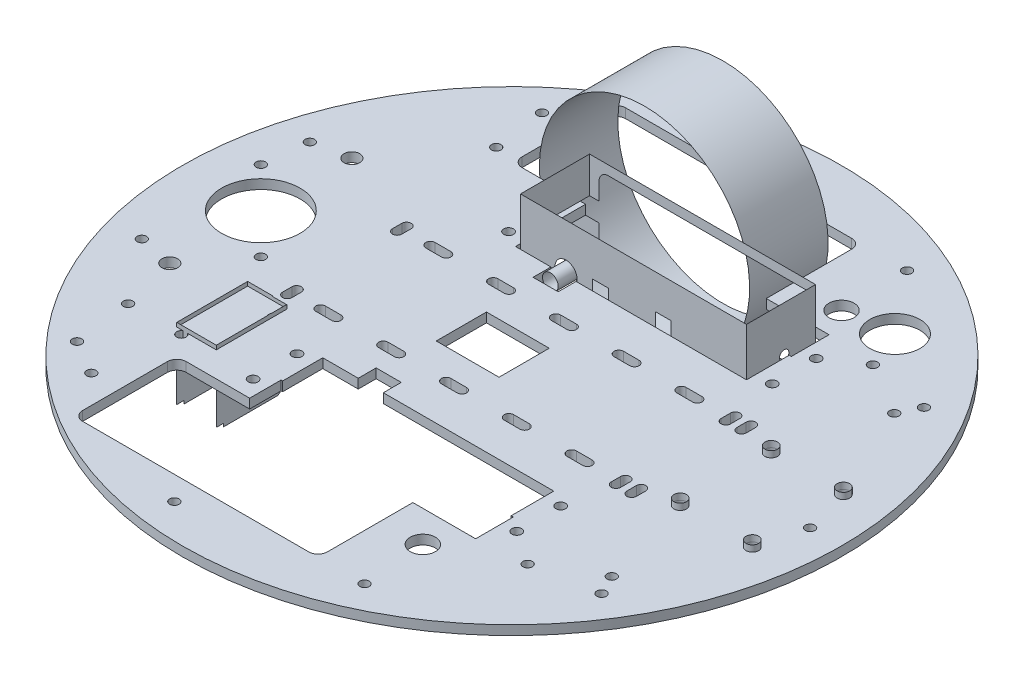
SolidWorks part; units mm, degrees
ref_plane "前基準面" through (0, 0, 0) normal (0, 0, 1) x (1, 0, 0)
ref_plane "上基準面" through (0, 0, 0) normal (0, 1, 0) x (1, 0, 0)
ref_plane "右基準面" through (0, 0, 0) normal (1, 0, 0) x (0, 0, -1)
sketch "草圖2" plane through (0, 0, 0) normal (0, 1, 0) x (1, 0, 0)
  line L1 (-60, 60) -> (60, 60) construction
  line L2 (-60, 60) -> (-60, -60) construction
  line L3 (-60, -60) -> (60, -60) construction
  line L4 (60, 60) -> (60, -60) construction
  line L5 (-60, 60) -> (60, -60) construction
  line L6 (-60, -60) -> (60, 60) construction
  circle A1 centre (0, 0) radius 100
  point P0 (0, 0)
  dimension "D1" = 120
  dimension "D3" = 200
  dimension "D2" = 120
extrude "填料-伸長1" add sketch "草圖2" along normal blind 3
sketch "草圖4" plane through (0, 3, 0) normal (0, 1, 0) x (1, 0, 0)
  line L0 (0, 0) -> (-80, 0) construction
  circle A1 centre (-80, 0) radius 12.5
  dimension "D2" = 25
  dimension "D1" = 80
extrude "除料-伸長2" cut sketch "草圖4" against normal blind 3
sketch "草圖5" plane through (0, 3, 0) normal (0, 1, 0) x (1, 0, 0)
  line L1 (-60, 55) -> (60, 55) construction
  line L2 (-60, 55) -> (-60, -55) construction
  line L3 (-60, -55) -> (60, -55) construction
  line L4 (60, 55) -> (60, -55) construction
  line L5 (-60, 55) -> (60, -55) construction
  line L6 (-60, -55) -> (60, 55) construction
  circle A0 centre (-60, 55) radius 1.5
  circle A1 centre (-60, -55) radius 1.5
  circle A2 centre (60, -55) radius 1.5
  circle A3 centre (60, 55) radius 1.5
  point P0 (0, 0)
  dimension "D3" = 3
  dimension "D4" = 3
  dimension "D5" = 3
  dimension "D6" = 3
  dimension "D1" = 120
  dimension "D2" = 110
extrude "除料-伸長3" cut sketch "草圖5" against normal blind 3
sketch "草圖6" plane through (0, 3, 0) normal (0, 1, 0) x (1, 0, 0)
  line L0 (0, 0) -> (126.0142, -2.0364) construction
  circle A0 centre (40, 65) radius 4
  circle A1 centre (37.8789, -66.2585) radius 4
  dimension "D1" = 8
  dimension "D2" = 40
  dimension "D3" = 65
extrude "除料-伸長4" cut sketch "草圖6" against normal blind 10
sketch "草圖7" plane through (0, 3, 0) normal (0, 1, 0) x (1, 0, 0)
  line L0 (0, 0) -> (-120.1853, 0) construction
  circle A1 centre (-70, -43.1259) radius 2.3
  circle A2 centre (-70, 43.1259) radius 2.3
  dimension "D1" = 43.1259
  dimension "D2" = 43.1259
  dimension "D3" = 70
sketch "草圖8" plane through (0, 3, 0) normal (0, 1, 0) x (1, 0, 0)
  line L0 (0, 0) -> (-129.4635, 0) construction
  line L2 (-99.2157, 12.5) -> (-111.2157, 12.5)
  line L3 (-99.2157, 12.5) -> (-99.2157, -12.5)
  line L4 (-99.2157, -12.5) -> (-111.2157, -12.5)
  line L5 (-114.2157, 9.5) -> (-114.2157, -9.5)
  circle A0 centre (0, 0) radius 100 construction
  arc A1 (-111.2157, -12.5) -> (-114.2157, -9.5) centre (-111.2157, -9.5) cw
  arc A2 (-111.2157, 12.5) -> (-114.2157, 9.5) centre (-111.2157, 9.5) ccw
  point P13 (-114.2157, -12.5)
  point P16 (-114.2157, 12.5)
  dimension "D3" = 3
  dimension "D1" = 25
  dimension "D2" = 15
extrude "填料-伸長2" add sketch "草圖8" against normal up to surface (3 mm away) up to face at (40, 0, -61)
sketch "草圖11" plane through (0, 3, 0) normal (0, 1, 0) x (1, 0, 0)
  line L0 (-114.2157, 0) -> (0, 0) construction
  line L1 (-114.2157, 9.5) -> (-114.2157, -9.5) construction
  line L2 (-80, 12.5) -> (-80, -12.5) construction
  circle A0 centre (-80, 0) radius 12.5 construction
  circle A1 centre (-80, -29) radius 2.5
  circle A2 centre (-80, 29) radius 2.5
  dimension "D1" = 5
  dimension "D2" = 29
  dimension "D3" = 0
extrude "除料-伸長9" cut sketch "草圖11" against normal blind 10
sketch "草圖12" plane through (0, 3, 0) normal (0, 1, 0) x (1, 0, 0)
  circle A0 centre (0, 0) radius 100
  circle A1 centre (0, 0) radius 174.0467
extrude "除料-伸長10" cut sketch "草圖12" against normal blind 10
surface "曲面-偏移1" parameters "D1"=0
sketch "草圖13" plane through (0, 3, 0) normal (0, 1, 0) x (1, 0, 0)
  line L0 (43.2344, 53.5) -> (43.2344, 31.5) construction
  line L1 (-28.7656, 53.5) -> (43.2344, 53.5) construction
  line L2 (-28.7656, 31.5) -> (-28.7656, 53.5) construction
  line L3 (43.2344, 31.5) -> (-28.7656, 31.5) construction
  line L4 (43.2344, 53.5) -> (43.2344, 31.5) construction
  line L5 (21.7344, 53.5) -> (43.2344, 53.5) construction
  line L6 (-28.7656, 31.5) -> (-28.7656, 53.5) construction
  line L7 (43.2344, 31.5) -> (-10.2656, 31.5) construction
  line L8 (-16.7656, 33.5) -> (-16.7656, 26.5) construction
  line L10 (-18.2656, 30.7) -> (-18.2656, 25)
  line L11 (-18.2656, 25) -> (-10.2656, 25)
  line L12 (-10.2656, 30.7) -> (-10.2656, 25)
  line L13 (-16.7656, 26.5) -> (-11.7656, 26.5) construction
  line L14 (19.2344, 81.5) -> (-47.7656, 81.5) construction
  line L15 (-50.2656, 53.5) -> (-29.5656, 53.5)
  line L16 (-50.2656, 53.5) -> (-50.2656, 83.5)
  line L17 (-50.2656, 83.5) -> (21.7344, 83.5)
  line L18 (21.7344, 54.3) -> (21.7344, 83.5)
  line L19 (-47.7656, 56.5) -> (19.2344, 56.5) construction
  line L20 (-47.7656, 56.5) -> (19.2344, 56.5) construction
  line L21 (19.2344, 81.5) -> (-47.7656, 81.5) construction
  line L22 (0, 0) -> (91.0786, 0) construction
  line L23 (21.7344, -53.5) -> (43.2344, -53.5) construction
  line L24 (-28.7656, -31.5) -> (-28.7656, -53.5) construction
  line L25 (43.2344, -31.5) -> (-28.7656, -31.5) construction
  line L26 (43.2344, -53.5) -> (43.2344, -31.5) construction
  line L27 (-50.2656, -83.5) -> (21.7344, -83.5)
  line L28 (21.7344, -54.3) -> (21.7344, -83.5)
  line L29 (-50.2656, -53.5) -> (-29.5656, -53.5)
  line L30 (-50.2656, -53.5) -> (-50.2656, -83.5)
  line L31 (44.0344, 30.7) -> (-10.2656, 30.7)
  line L32 (-29.5656, 30.7) -> (-29.5656, 53.5)
  line L33 (21.7344, 54.3) -> (44.0344, 54.3)
  line L34 (44.0344, 54.3) -> (44.0344, 30.7)
  line L35 (-28.7656, 53.5) -> (43.2344, 53.5) construction
  line L36 (-29.5656, -30.7) -> (-29.5656, -53.5)
  line L37 (21.7344, -54.3) -> (44.0344, -54.3)
  line L38 (44.0344, -54.3) -> (44.0344, -30.7)
  line L39 (44.0344, -30.7) -> (-29.5656, -30.7) construction
  line L40 (-28.7656, -53.5) -> (43.2344, -53.5) construction
  line L41 (-29.5656, 54.3) -> (44.0344, 54.3) construction
  line L42 (-29.5656, 30.7) -> (-29.5656, 54.3) construction
  line L43 (-29.5656, -54.3) -> (44.0344, -54.3) construction
  line L44 (-29.5656, -30.7) -> (-29.5656, -54.3) construction
  line L45 (-18.2656, 31.5) -> (-28.7656, 31.5) construction
  line L46 (43.2344, 31.5) -> (-28.7656, 31.5) construction
  line L47 (-10.2656, -30.7) -> (-10.2656, -25)
  line L48 (-18.2656, -25) -> (-10.2656, -25)
  line L49 (-18.2656, -30.7) -> (-18.2656, -25)
  line L50 (-18.2656, 30.7) -> (-29.5656, 30.7)
  line L51 (44.0344, 30.7) -> (-29.5656, 30.7) construction
  line L52 (-29.5656, -30.7) -> (-18.2656, -30.7)
  line L53 (-10.2656, -30.7) -> (44.0344, -30.7)
  circle A0 centre (-34.7656, 34.5) radius 1.55 construction
  circle A1 centre (49.2344, 48.5) radius 1.55 construction
  circle A2 centre (-34.7656, 34.5) radius 1.55 construction
  circle A3 centre (-34.7656, 48.5) radius 1.55 construction
  circle A4 centre (-34.7656, 34.5) radius 1.55
  circle A5 centre (49.2344, 48.5) radius 1.55
  circle A6 centre (-34.7656, 34.5) radius 1.55
  circle A7 centre (-34.7656, 48.5) radius 1.55
  circle A8 centre (-34.7656, -34.5) radius 1.55
  circle A9 centre (49.2344, -48.5) radius 1.55
  circle A10 centre (-34.7656, -34.5) radius 1.55
  circle A11 centre (-34.7656, -48.5) radius 1.55
  dimension "D1" = 1.5
  dimension "D2" = 1.5
  dimension "D3" = 8
  dimension "D4" = 2
  dimension "D5" = 72
  dimension "D6" = 2.5
  dimension "D7" = 0.8
  dimension "D8" = 0.8
extrude "除料-伸長12" cut sketch "草圖13" against normal blind 3
surface "曲面-偏移2" parameters "D1"=0
sketch "草圖14" plane through (0, 3, 0) normal (0, 1, 0) x (1, 0, 0)
  circle A0 centre (91.0992, 14.5) radius 2 construction
  circle A1 centre (91.0992, -14.5) radius 2 construction
  circle A2 centre (68.0992, -14.5) radius 2 construction
  circle A3 centre (91.0992, -14.5) radius 2 construction
  circle A4 centre (91.0992, 14.5) radius 2
  circle A5 centre (91.0992, -14.5) radius 2
  circle A6 centre (68.0992, -14.5) radius 2
  circle A7 centre (91.0992, -14.5) radius 2
sketch "草圖16" plane through (0, 3, 0) normal (0, 1, 0) x (1, 0, 0)
  line L1 (-61.2924, -22.8971) -> (-48.7028, -22.8971)
  line L2 (-61.2924, -22.8971) -> (-61.2924, -45.5029)
  line L3 (-61.2924, -45.5029) -> (-48.7028, -45.5029)
  line L4 (-48.7028, -22.8971) -> (-48.7028, -45.5029)
  arc A0 (-54.3908, -48.9614) -> (-55.5908, -48.962) centre (-54.9912, -48.1) ccw construction
  arc A1 (-55.6044, -19.4386) -> (-54.4044, -19.438) centre (-55.004, -20.3) ccw construction
  arc A2 (-54.3908, -48.9614) -> (-55.5908, -48.962) centre (-54.9912, -48.1) ccw
  arc A3 (-55.6044, -19.4386) -> (-54.4044, -19.438) centre (-55.004, -20.3) ccw
  circle A4 centre (-55.004, -20.3) radius 1.05
  circle A5 centre (-54.9912, -48.1) radius 1.05
  circle M24 centre (-80, -29) radius 2.5
extrude "除料-伸長14" cut sketch "草圖16" against normal blind 3 contours L4 L1 L2 L3 M24 | A2 A5 | A3 A4
sketch "草圖17" plane through (0, 0, 0) normal (0, -1, 0) x (1, 0, 0)
  line L4 (25.5633, 13) -> (25.5633, 22) construction
  line L8 (25.5633, 13) -> (25.5633, 22) construction
  line L9 (25.5633, 22) -> (5.5633, 22) construction
  line L10 (5.5633, 22) -> (5.5633, 13) construction
  line L11 (5.5633, 13) -> (25.5633, 13) construction
  line L12 (25.5633, 13) -> (25.5633, 22) construction
  line L13 (25.5633, 22) -> (5.5633, 22) construction
  line L14 (5.5633, 22) -> (5.5633, 13) construction
  line L15 (5.5633, 13) -> (25.5633, 13) construction
  line L16 (25.5633, 17.5) -> (-33.0085, 17.5) construction
  line L17 (25.5633, 17.5) -> (-33.0085, 17.5) construction
  line L18 (36.5344, 17.5) -> (41.5344, 17.5) construction
  line L19 (36.5344, 19) -> (41.5344, 19)
  line L20 (36.5344, 16) -> (41.5344, 16)
  line L21 (44.0344, 54.3) -> (44.0344, 30.7) construction
  line L22 (16.5344, 16) -> (21.5344, 16)
  line L23 (16.5344, 19) -> (21.5344, 19)
  line L24 (16.5344, 17.5) -> (21.5344, 17.5) construction
  line L25 (-3.4656, 16) -> (1.5344, 16)
  line L26 (-3.4656, 19) -> (1.5344, 19)
  line L27 (-3.4656, 17.5) -> (1.5344, 17.5) construction
  line L28 (-23.4656, 16) -> (-18.4656, 16)
  line L29 (-23.4656, 19) -> (-18.4656, 19)
  line L30 (-23.4656, 17.5) -> (-18.4656, 17.5) construction
  line L31 (0, 0) -> (20.4182, 0) construction
  line L32 (36.5344, -17.5) -> (41.5344, -17.5) construction
  line L33 (36.5344, -19) -> (41.5344, -19)
  line L34 (36.5344, -16) -> (41.5344, -16)
  line L35 (16.5344, -17.5) -> (21.5344, -17.5) construction
  line L36 (16.5344, -19) -> (21.5344, -19)
  line L37 (16.5344, -16) -> (21.5344, -16)
  line L38 (-3.4656, -17.5) -> (1.5344, -17.5) construction
  line L39 (-3.4656, -19) -> (1.5344, -19)
  line L40 (-3.4656, -16) -> (1.5344, -16)
  line L41 (-23.4656, -17.5) -> (-18.4656, -17.5) construction
  line L42 (-23.4656, -19) -> (-18.4656, -19)
  line L43 (-23.4656, -16) -> (-18.4656, -16)
  arc A0 (36.5344, 19) -> (36.5344, 16) centre (36.5344, 17.5) ccw
  arc A1 (41.5344, 16) -> (41.5344, 19) centre (41.5344, 17.5) ccw
  arc A2 (16.5344, 19) -> (16.5344, 16) centre (16.5344, 17.5) ccw
  arc A3 (21.5344, 16) -> (21.5344, 19) centre (21.5344, 17.5) ccw
  arc A4 (-3.4656, 19) -> (-3.4656, 16) centre (-3.4656, 17.5) ccw
  arc A5 (1.5344, 16) -> (1.5344, 19) centre (1.5344, 17.5) ccw
  arc A6 (-23.4656, 19) -> (-23.4656, 16) centre (-23.4656, 17.5) ccw
  arc A7 (-18.4656, 16) -> (-18.4656, 19) centre (-18.4656, 17.5) ccw
  arc A8 (36.5344, -19) -> (36.5344, -16) centre (36.5344, -17.5) cw
  arc A9 (41.5344, -16) -> (41.5344, -19) centre (41.5344, -17.5) cw
  arc A10 (16.5344, -19) -> (16.5344, -16) centre (16.5344, -17.5) cw
  arc A11 (21.5344, -16) -> (21.5344, -19) centre (21.5344, -17.5) cw
  arc A12 (-3.4656, -19) -> (-3.4656, -16) centre (-3.4656, -17.5) cw
  arc A13 (1.5344, -16) -> (1.5344, -19) centre (1.5344, -17.5) cw
  arc A14 (-23.4656, -19) -> (-23.4656, -16) centre (-23.4656, -17.5) cw
  arc A15 (-18.4656, -16) -> (-18.4656, -19) centre (-18.4656, -17.5) cw
  point P15 (39.0344, 17.5)
  point P25 (19.0344, 17.5)
  point P33 (-0.9656, 17.5)
  point P40 (-20.9656, 17.5)
  point P48 (39.0344, -17.5)
  point P55 (19.0344, -17.5)
  point P62 (-0.9656, -17.5)
  point P69 (-20.9656, -17.5)
  dimension "D3" = 1.5
  dimension "D1" = 3
  dimension "D2" = 5
  dimension "D4" = 5
  dimension "D5" = 4
extrude "除料-伸長15" cut sketch "草圖17" against normal blind 3
sketch "草圖18" plane through (0, 0, 0) normal (0, -1, 0) x (1, 0, 0)
  line L0 (-50.2656, 53.5) -> (-50.2656, 83.5) construction
  line L1 (3.8844, -8) -> (-16.1156, -8)
  line L2 (3.8844, -8) -> (3.8844, 8)
  line L3 (3.8844, 8) -> (-16.1156, 8)
  line L4 (-16.1156, -8) -> (-16.1156, 8)
  point P0 (0, 0)
  dimension "D1" = 8
  dimension "D2" = 8
  dimension "D3" = 20
  dimension "D4" = 54.15
extrude "除料-伸長16" cut sketch "草圖18" against normal blind 3
sketch "草圖19" plane through (0, 3, 0) normal (0, 1, 0) x (1, 0, 0)
  line L0 (-80, 0) -> (-86.6044, 6.6044) construction
  line L1 (-80, 0) -> (0, 0) construction
  line L2 (-80, 0) -> (-48.2867, -31.7133) construction
  circle A0 centre (-92.7279, 12.7279) radius 1.5
  circle A1 centre (-67.2721, -12.7279) radius 1.5
  dimension "D2" = 3
  dimension "D3" = 3
  dimension "D1" = 135
  dimension "D4" = 18
  dimension "D5" = 18
extrude "除料-伸長17" cut sketch "草圖19" against normal blind 3
sketch "草圖20" plane through (0, 0, 0) normal (0, -1, 0) x (1, 0, 0)
  circle A0 centre (0, 0) radius 95 construction
  circle A1 centre (95, 0) radius 1.5
  circle A2 centre (79.9191, -51.3609) radius 1.5
  circle A3 centre (39.4644, -86.415) radius 1.5
  circle A4 centre (-13.5199, -94.033) radius 1.5
  circle A5 centre (-62.2118, -71.7962) radius 1.5
  circle A6 centre (-91.1518, -26.7646) radius 1.5
  circle A7 centre (-91.1518, 26.7646) radius 1.5
  circle A8 centre (-62.2118, 71.7962) radius 1.5
  circle A9 centre (-13.5199, 94.033) radius 1.5
  circle A10 centre (39.4644, 86.415) radius 1.5
  circle A11 centre (79.9191, 51.3609) radius 1.5
  point P27 (0, 0)
  dimension "D1" = 190
  dimension "D2" = 3
  dimension "D3" = 11
extrude "除料-伸長18" cut sketch "草圖20" against normal blind 3
sketch "草圖21" plane through (0, 0, 0) normal (0, -1, 0) x (1, 0, 0)
  line L0 (52.142, -19) -> (52.142, -16) construction
  line L1 (50.642, -19) -> (50.642, -16)
  line L2 (53.642, -19) -> (53.642, -16)
  line L3 (57.142, -19) -> (57.142, -16) construction
  line L4 (55.642, -19) -> (55.642, -16)
  line L5 (58.642, -19) -> (58.642, -16)
  line L6 (52.142, -17.5) -> (57.142, -17.5) construction
  line L7 (0, 0) -> (80.616, 0) construction
  line L8 (39.0344, -16) -> (39.0344, -19) construction
  line L9 (41.5344, -16) -> (36.5344, -16) construction
  line L10 (36.5344, -19) -> (41.5344, -19) construction
  line L11 (39.0344, -17.5) -> (48.889, -17.5) construction
  line L12 (57.142, 19) -> (57.142, 16) construction
  line L13 (55.642, 19) -> (55.642, 16)
  line L14 (58.642, 19) -> (58.642, 16)
  line L15 (52.142, 19) -> (52.142, 16) construction
  line L16 (50.642, 19) -> (50.642, 16)
  line L17 (53.642, 19) -> (53.642, 16)
  arc A0 (50.642, -19) -> (53.642, -19) centre (52.142, -19) ccw
  arc A1 (53.642, -16) -> (50.642, -16) centre (52.142, -16) ccw
  arc A2 (55.642, -19) -> (58.642, -19) centre (57.142, -19) ccw
  arc A3 (58.642, -16) -> (55.642, -16) centre (57.142, -16) ccw
  arc A4 (55.642, 19) -> (58.642, 19) centre (57.142, 19) cw
  arc A5 (58.642, 16) -> (55.642, 16) centre (57.142, 16) cw
  arc A6 (50.642, 19) -> (53.642, 19) centre (52.142, 19) cw
  arc A7 (53.642, 16) -> (50.642, 16) centre (52.142, 16) cw
  point P2 (52.142, -17.5)
  point P7 (53.642, -17.5)
  point P10 (57.142, -17.5)
  point P31 (57.142, 17.5)
  point P38 (52.142, 17.5)
  dimension "D1" = 3
  dimension "D2" = 3
  dimension "D3" = 5
  dimension "D4" = 3
  dimension "D5" = 3
extrude "除料-伸長19" cut sketch "草圖21" against normal blind 3
fillet "圓角1" radius 2 6 edges at (21.7344, 1.5, 83.5) (-50.2656, 1.5, 83.5) (-50.2656, 1.5, 53.5) (21.7344, 1.5, -83.5) (-50.2656, 1.5, -53.5) (-50.2656, 1.5, -83.5)
extrude "除料-伸長21" cut sketch "草圖14" against normal blind 10 contours A4 | A5 | A6
sketch "草圖22" plane through (0, 3, 0) normal (0, 1, 0) x (1, 0, 0)
  circle A0 centre (0, 0) radius 100
  circle A1 centre (0, 0) radius 105
  dimension "D1" = 5
  dimension "D2" = 200
extrude "填料-伸長3" add sketch "草圖22" against normal up to surface (3 mm away) up to face at (91.0992, 0, -12.5)
sketch "草圖23" plane through (0, 3, 0) normal (0, 1, 0) x (1, 0, 0)
  line L0 (-48.2656, -53.5) -> (-53.2656, -53.5) construction
  line L1 (-50.2656, -55.5) -> (-50.2656, -81.5) construction
  line L2 (-53.2656, -53.5) -> (24.7344, -53.5)
  line L3 (-53.2656, -53.5) -> (-53.2656, -86.5)
  line L4 (-53.2656, -86.5) -> (24.7344, -86.5)
  line L5 (24.7344, -53.5) -> (24.7344, -86.5)
  line L6 (-48.2656, -83.5) -> (19.7344, -83.5) construction
  line L7 (21.7344, -54.3) -> (21.7344, -81.5) construction
  line L8 (-46.7917, 53.5) -> (-53.2656, 53.5) construction
  line L9 (-48.2656, 53.5) -> (-29.5656, 53.5) construction
  line L10 (-50.2656, 55.5) -> (-50.2656, 81.5) construction
  line L11 (-53.2656, 53.5) -> (24.7344, 53.5)
  line L12 (-53.2656, 53.5) -> (-53.2656, 86.5)
  line L13 (-53.2656, 86.5) -> (24.7344, 86.5)
  line L14 (24.7344, 53.5) -> (24.7344, 86.5)
  line L15 (-48.2656, 83.5) -> (19.7344, 83.5) construction
  line L16 (21.7344, 54.3) -> (21.7344, 81.5) construction
  dimension "D1" = 3
  dimension "D2" = 3
  dimension "D3" = 3
  dimension "D4" = 3
  dimension "D5" = 3
  dimension "D6" = 3
extrude "除料-伸長22" cut sketch "草圖23" against normal up to next
fillet "圓角2" radius 3 6 edges at (24.7344, 1.5, -86.5) (-53.2656, 1.5, -53.5) (-53.2656, 1.5, -86.5) (24.7344, 1.5, 86.5) (-53.2656, 1.5, 86.5) (-53.2656, 1.5, 53.5)
sketch "草圖25" plane through (0, 3, 0) normal (0, 1, 0) x (1, 0, 0)
  line L1 (-29.5656, 53.5) -> (-30.5656, 53.5)
  line L2 (-29.5656, 53.5) -> (-29.5656, 45.5)
  line L3 (-29.5656, 45.5) -> (-30.5656, 45.5)
  line L4 (-30.5656, 53.5) -> (-30.5656, 45.5)
  dimension "D1" = 1
  dimension "D2" = 8
sketch "草圖26" plane through (0, 3, 0) normal (0, 1, 0) x (1, 0, 0)
  line L1 (-37.54, 51.3996) -> (-32.3697, 51.3996)
  line L2 (-37.54, 51.3996) -> (-37.54, 31.7189)
  line L3 (-37.54, 31.7189) -> (-32.3697, 31.7189)
  line L4 (-32.3697, 51.3996) -> (-32.3697, 31.7189)
  line L5 (46.5197, 51.3996) -> (52.0237, 51.3996)
  line L6 (46.5197, 51.3996) -> (46.5197, 45.3953)
  line L7 (46.5197, 45.3953) -> (52.0237, 45.3953)
  line L8 (52.0237, 51.3996) -> (52.0237, 45.3953)
  line L9 (-37.54, -31.287) -> (-32.3697, -31.287)
  line L10 (-37.54, -31.287) -> (-37.54, -51.5386)
  line L11 (-37.54, -51.5386) -> (-32.3697, -51.5386)
  line L12 (-32.3697, -31.287) -> (-32.3697, -51.5386)
  line L13 (46.5197, -44.6292) -> (52.0237, -44.6292)
  line L14 (46.5197, -44.6292) -> (46.5197, -51.5386)
  line L15 (46.5197, -51.5386) -> (52.0237, -51.5386)
  line L16 (52.0237, -44.6292) -> (52.0237, -51.5386)
extrude "填料-伸長4" add sketch "草圖26" against normal up to surface (3 mm away) up to face at (-10.9737, 0, 52.3681)
surface "曲面-偏移3" parameters "D1"=0
sketch "草圖27" plane through (0, 0, 0) normal (0, -1, 0) x (1, 0, 0)
  circle A0 centre (-34.7656, 47.7) radius 1.55 construction
  circle A1 centre (-34.7656, 33.7) radius 1.55 construction
  circle A3 centre (49.2344, 47.7) radius 1.55 construction
  circle A4 centre (49.2344, 33.7) radius 1.55 construction
  circle A5 centre (49.2344, -33.7) radius 1.55 construction
  circle A6 centre (49.2344, -47.7) radius 1.55 construction
  circle A7 centre (-34.7656, -33.7) radius 1.55 construction
  circle A8 centre (-34.7656, -47.7) radius 1.55 construction
  circle A9 centre (-34.7656, 47.7) radius 1.55
  circle A10 centre (-34.7656, 33.7) radius 1.55
  circle A11 centre (49.2344, 47.7) radius 1.55
  circle A12 centre (49.2344, 33.7) radius 1.55
  circle A13 centre (49.2344, -33.7) radius 1.55
  circle A14 centre (49.2344, -47.7) radius 1.55
  circle A15 centre (-34.7656, -33.7) radius 1.55
  circle A16 centre (-34.7656, -47.7) radius 1.55
extrude "除料-伸長23" cut sketch "草圖27" against normal blind 10
sketch "草圖28" plane through (0, 0, 0) normal (0, -1, 0) x (1, 0, 0)
  line L5 (24.7344, -83.5) -> (24.7344, -54.3) construction
  line L6 (24.7344, -56.3) -> (44.7344, -56.3)
  line L7 (24.7344, -56.3) -> (24.7344, -44.3)
  line L8 (24.7344, -44.3) -> (44.7344, -44.3)
  line L9 (44.7344, -56.3) -> (44.7344, -44.3)
  line L10 (24.7344, -54.3) -> (44.0344, -54.3) construction
  line L11 (0, 0) -> (129.2997, 0) construction
  line L12 (24.7344, 44.3) -> (44.7344, 44.3)
  line L13 (44.7344, 56.3) -> (44.7344, 44.3)
  line L14 (24.7344, 56.3) -> (44.7344, 56.3)
  line L15 (24.7344, 56.3) -> (24.7344, 44.3)
  line L16 (-29.5656, 43.5) -> (-30.0656, 43.5)
  line L17 (-29.5656, -53.5) -> (-30.0656, -53.5)
  line L18 (-29.5656, -53.5) -> (-29.5656, -43.5)
  line L19 (-29.5656, -43.5) -> (-30.0656, -43.5)
  line L20 (-30.0656, -53.5) -> (-30.0656, -43.5)
  line L21 (-30.0656, 53.5) -> (-30.0656, 43.5)
  line L22 (-29.5656, 53.5) -> (-30.0656, 53.5)
  line L23 (-29.5656, 53.5) -> (-29.5656, 43.5)
  dimension "D1" = 2
  dimension "D2" = 20
  dimension "D3" = 10
  dimension "D4" = 0.5
  dimension "D5" = 10
extrude "除料-伸長24" cut sketch "草圖28" against normal blind 10
sketch "草圖29" plane through (0, 0, 0) normal (0, -1, 0) x (1, 0, 0)
  line L1 (-64.6454, 17.591) -> (-45.7636, 17.591)
  line L2 (-64.6454, 17.591) -> (-64.6454, 50.6341)
  line L3 (-64.6454, 50.6341) -> (-45.7636, 50.6341)
  line L4 (-45.7636, 17.591) -> (-45.7636, 50.6341)
  line L5 (-62.9408, 52.0765) -> (-56.3846, 52.0765)
  line L6 (-62.9408, 52.0765) -> (-62.9408, 57.7148)
  line L7 (-62.9408, 57.7148) -> (-56.3846, 57.7148)
  line L8 (-56.3846, 52.0765) -> (-56.3846, 57.7148)
extrude "填料-伸長5" add sketch "草圖29" against normal up to surface (3 mm away) up to face at (-7.1194, 3, 50.7959)
sketch "草圖30" plane through (0, 0, 0) normal (0, -1, 0) x (1, 0, 0)
  circle A0 centre (76.8047, 45) radius 1.5 construction
  circle A1 centre (76.8047, -45) radius 1.5 construction
  circle A2 centre (-73.1869, 65.3805) radius 1.5 construction
  circle A3 centre (-58.5382, 46.798) radius 1.5 construction
  circle A4 centre (-75.4794, 46.798) radius 1.5 construction
  circle A5 centre (76.8047, 45) radius 1.5
  circle A6 centre (76.8047, -45) radius 1.5
  circle A7 centre (-73.1869, 65.3805) radius 1.5
  circle A8 centre (-58.5382, 46.798) radius 1.5
  circle A9 centre (-75.4794, 46.798) radius 1.5
extrude "除料-伸長25" cut sketch "草圖30" against normal blind 5
sketch "草圖31" plane through (0, 0, 0) normal (0, -1, 0) x (1, 0, 0)
  circle A0 centre (55.0159, -67.0054) radius 8
  point P2 (55.3468, -67.5018)
  point P3 (55.0159, -67.0054)
  dimension "D1" = 16
extrude "除料-伸長26" cut sketch "草圖31" against normal blind 5
sketch "草圖32" plane through (0, 0, 0) normal (0, -1, 0) x (1, 0, 0)
  line L0 (68.0992, 14.5) -> (91.0992, 14.5) construction
  line L1 (79.5992, 14.5) -> (79.5992, -13.533) construction
  circle A0 centre (91.0992, -14.5) radius 2 construction
  circle A1 centre (91.0992, -14.5) radius 2
  circle A2 centre (68.0992, -14.5) radius 2
extrude "除料-伸長27" cut sketch "草圖32" against normal blind 5
sketch "草圖33" plane through (0, 0, 0) normal (0, -1, 0) x (1, 0, 0)
  line L0 (-23.4656, -19) -> (-18.4656, -19) construction
  line L1 (-18.4656, -16) -> (-23.4656, -16) construction
  line L2 (-18.4656, 19) -> (-23.4656, 19) construction
  line L3 (-23.4656, 16) -> (-18.4656, 16) construction
  line L4 (-23.4656, -19) -> (-18.4656, -19)
  line L5 (-18.4656, -16) -> (-23.4656, -16)
  line L6 (-18.4656, 19) -> (-23.4656, 19)
  line L7 (-23.4656, 16) -> (-18.4656, 16)
  line L8 (-43.4656, 16) -> (-38.4656, 16)
  line L9 (-38.4656, 19) -> (-43.4656, 19)
  line L10 (-38.4656, -16) -> (-43.4656, -16)
  line L11 (-43.4656, -19) -> (-38.4656, -19)
  arc A0 (-18.4656, -19) -> (-18.4656, -16) centre (-18.4656, -17.5) ccw construction
  arc A1 (-23.4656, -16) -> (-23.4656, -19) centre (-23.4656, -17.5) ccw construction
  arc A2 (-23.4656, 19) -> (-23.4656, 16) centre (-23.4656, 17.5) ccw construction
  arc A3 (-18.4656, 16) -> (-18.4656, 19) centre (-18.4656, 17.5) ccw construction
  arc A4 (-18.4656, -19) -> (-18.4656, -16) centre (-18.4656, -17.5) ccw
  arc A5 (-23.4656, -16) -> (-23.4656, -19) centre (-23.4656, -17.5) ccw
  arc A6 (-23.4656, 19) -> (-23.4656, 16) centre (-23.4656, 17.5) ccw
  arc A7 (-18.4656, 16) -> (-18.4656, 19) centre (-18.4656, 17.5) ccw
  arc A8 (-43.4656, 19) -> (-43.4656, 16) centre (-43.4656, 17.5) ccw
  arc A9 (-38.4656, 16) -> (-38.4656, 19) centre (-38.4656, 17.5) ccw
  arc A10 (-38.4656, -19) -> (-38.4656, -16) centre (-38.4656, -17.5) ccw
  arc A11 (-43.4656, -16) -> (-43.4656, -19) centre (-43.4656, -17.5) ccw
  dimension "D1" = 2
extrude "除料-伸長28" cut sketch "草圖33" against normal blind 5
sketch "草圖34" plane through (0, 0, 0) normal (0, -1, 0) x (1, 0, 0)
  line L0 (50.642, -16) -> (50.642, -19) construction
  line L1 (53.642, -19) -> (53.642, -16) construction
  line L2 (50.642, 19) -> (50.642, 16) construction
  line L3 (53.642, 16) -> (53.642, 19) construction
  line L4 (50.642, -16) -> (50.642, -19)
  line L5 (53.642, -19) -> (53.642, -16)
  line L6 (50.642, 19) -> (50.642, 16)
  line L7 (53.642, 16) -> (53.642, 19)
  line L8 (-0.2168, 39.9501) -> (-0.2168, -36.9181) construction
  line L9 (-51.0756, -16) -> (-51.0756, -19)
  line L10 (-54.0756, -19) -> (-54.0756, -16)
  line L11 (-51.0756, 19) -> (-51.0756, 16)
  line L12 (-54.0756, 16) -> (-54.0756, 19)
  arc A0 (50.642, -19) -> (53.642, -19) centre (52.142, -19) ccw construction
  arc A1 (53.642, -16) -> (50.642, -16) centre (52.142, -16) ccw construction
  arc A2 (50.642, 16) -> (53.642, 16) centre (52.142, 16) ccw construction
  arc A3 (53.642, 19) -> (50.642, 19) centre (52.142, 19) ccw construction
  arc A4 (50.642, -19) -> (53.642, -19) centre (52.142, -19) ccw
  arc A5 (53.642, -16) -> (50.642, -16) centre (52.142, -16) ccw
  arc A6 (50.642, 16) -> (53.642, 16) centre (52.142, 16) ccw
  arc A7 (53.642, 19) -> (50.642, 19) centre (52.142, 19) ccw
  arc A8 (-54.0756, -16) -> (-51.0756, -16) centre (-52.5756, -16) cw
  arc A9 (-51.0756, -19) -> (-54.0756, -19) centre (-52.5756, -19) cw
  arc A10 (-54.0756, 19) -> (-51.0756, 19) centre (-52.5756, 19) cw
  arc A11 (-51.0756, 16) -> (-54.0756, 16) centre (-52.5756, 16) cw
extrude "除料-伸長29" cut sketch "草圖34" against normal blind 5
